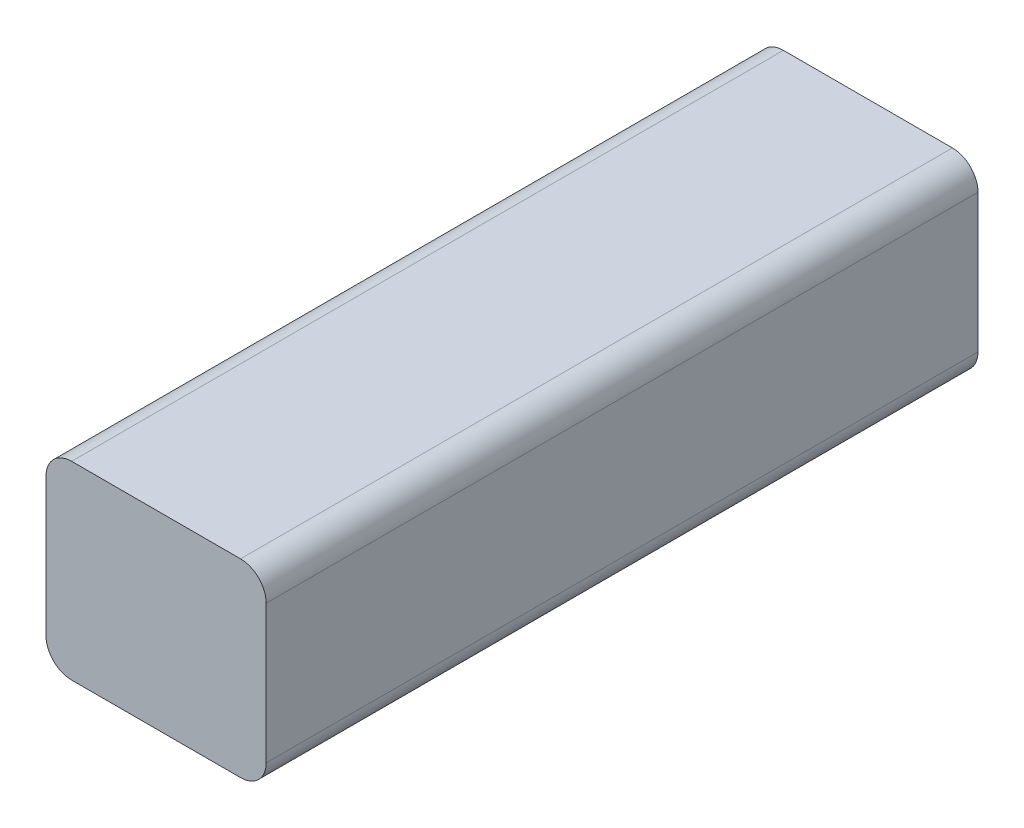
SolidWorks part; units mm, degrees
ref_plane "前视基准面" through (0, 0, 0) normal (0, 0, 1) x (1, 0, 0)
ref_plane "上视基准面" through (0, 0, 0) normal (0, 1, 0) x (1, 0, 0)
ref_plane "右视基准面" through (0, 0, 0) normal (1, 0, 0) x (0, 0, -1)
other "Configuration Table"
sketch "草图1" plane through (0, 0, 0) normal (0, 0, 1) x (1, 0, 0)
  line L1 (21.5, -18.5) -> (-21.5, -18.5)
  line L2 (21.5, -18.5) -> (21.5, 18.5)
  line L3 (21.5, 18.5) -> (-21.5, 18.5)
  line L4 (-21.5, -18.5) -> (-21.5, 18.5)
  line L5 (21.5, -18.5) -> (-21.5, 18.5) construction
  line L6 (21.5, 18.5) -> (-21.5, -18.5) construction
  point P0 (0, 0)
  dimension "D1" = 37
  dimension "D2" = 43
extrude "凸台-拉伸1" add sketch "草图1" along normal blind 139
fillet "圆角1" radius 5 4 edges at (21.5, -18.5, 69.5) (-21.5, -18.5, 69.5) (-21.5, 18.5, 69.5) (21.5, 18.5, 69.5)
